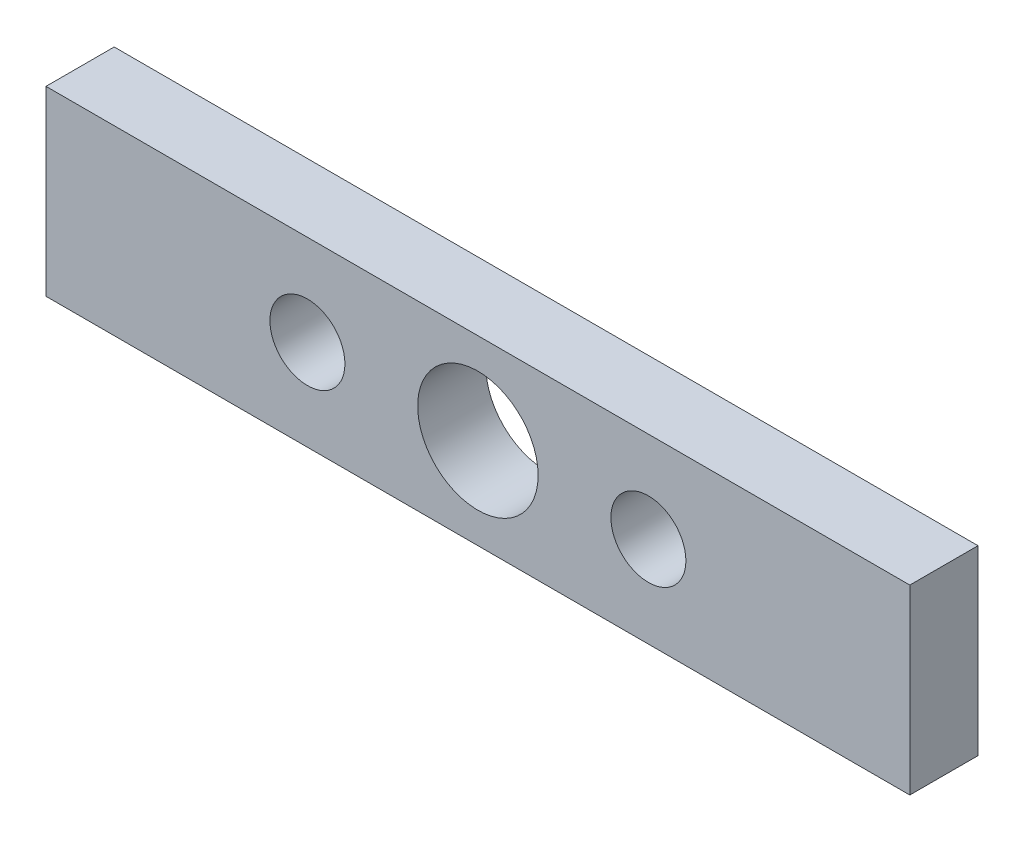
SolidWorks part; units mm, degrees
material "PTFE (general)"
ref_plane "Front Plane" through (0, 0, 0) normal (0, 0, 1) x (1, 0, 0)
ref_plane "Top Plane" through (0, 0, 0) normal (0, 1, 0) x (1, 0, 0)
ref_plane "Right Plane" through (0, 0, 0) normal (1, 0, 0) x (0, 0, -1)
sketch "Sketch1" plane through (0, 0, 0) normal (0, 0, 1) x (1, 0, 0)
  line L1 (-19, 0) -> (19, 0)
  line L2 (-19, 0) -> (-19, 8)
  line L3 (-19, 8) -> (19, 8)
  line L4 (19, 0) -> (19, 8)
  dimension "D1" = 8
  dimension "D2" = 38
extrude "Boss-Extrude1" add sketch "Sketch1" along normal blind 3
sketch "Sketch2" plane through (0, 0, 3) normal (0, 0, 1) x (1, 0, 0)
  line L0 (0, 0) -> (0, 8) construction
  line L1 (-19, 0) -> (19, 0) construction
  line L2 (19, 8) -> (-19, 8) construction
  line L3 (-19, 8) -> (-19, 0) construction
  line L4 (-19, 4) -> (19, 4) construction
  line L5 (19, 0) -> (19, 8) construction
  circle A0 centre (0, 4) radius 2.65
  circle A1 centre (-7.5, 4) radius 1.65
  circle A2 centre (7.5, 4) radius 1.65
  dimension "D1" = 5.3
  dimension "D2" = 3.3
  dimension "D3" = 7.5
  dimension "D4" = 15
extrude "Cut-Extrude1" cut sketch "Sketch2" against normal through all
